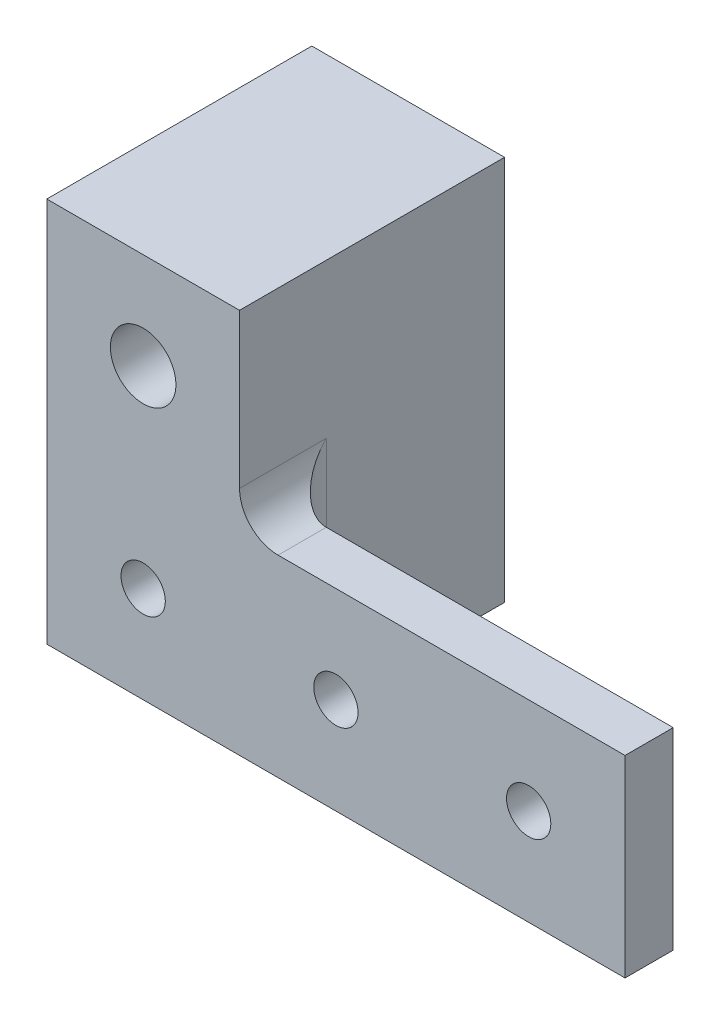
SolidWorks part; units mm, degrees
ref_plane "Front Plane" through (0, 0, 0) normal (0, 0, 1) x (1, 0, 0)
ref_plane "Top Plane" through (0, 0, 0) normal (0, 1, 0) x (1, 0, 0)
ref_plane "Right Plane" through (0, 0, 0) normal (1, 0, 0) x (0, 0, -1)
sketch "Sketch1" plane through (0, 0, 0) normal (0, 0, 1) x (1, 0, 0)
  line L0 (0, 0) -> (0, 50.8)
  line L1 (0, 50.8) -> (25.4, 50.8)
  line L2 (25.4, 50.8) -> (25.4, 25.4)
  line L3 (25.4, 25.4) -> (76.2, 25.4)
  line L4 (76.2, 25.4) -> (76.2, 0)
  line L5 (76.2, 0) -> (0, 0)
  dimension "D1" = 50.8
  dimension "D2" = 25.4
  dimension "3" = 76.2
extrude "Boss-Extrude1" add sketch "Sketch1" along normal blind 34.925
sketch "Sketch2" plane through (0, 0, 34.925) normal (0, 0, 1) x (1, 0, 0)
  line L0 (25.4, 50.8) -> (0, 50.8) construction
  line L1 (25.4, 25.4) -> (25.4, 50.8) construction
  line L2 (0, 0) -> (76.2, 0) construction
  circle A0 centre (12.7, 38.1) radius 2.921
  circle A1 centre (12.7, 12.7) radius 2.921
  circle A2 centre (38.1, 12.7) radius 2.921
  circle A3 centre (63.5, 12.7) radius 2.921
  dimension ".23" = 5.842
  dimension "D2" = 12.7
  dimension "D3" = 12.7
  dimension "D4" = 12.7
  dimension "D5" = 3
extrude "Cut-Extrude1" cut sketch "Sketch2" against normal through all
sketch "Sketch3" plane through (0, 0, 34.925) normal (0, 0, 1) x (1, 0, 0)
  line L0 (25.4, 50.8) -> (0, 50.8) construction
  line L1 (0, 0) -> (4.7625, 0)
  line L2 (0, 0) -> (0, 50.8)
  line L3 (0, 50.8) -> (4.7625, 50.8)
  line L4 (4.7625, 0) -> (4.7625, 50.8)
  dimension "D1" = 4.7625
sketch "Sketch4" plane through (0, 0, 0) normal (0, -1, 0) x (1, 0, 0)
  line L1 (76.2, 0) -> (25.4, 0)
  line L2 (76.2, 0) -> (76.2, 28.575)
  line L3 (76.2, 28.575) -> (25.4, 28.575)
  line L4 (25.4, 0) -> (25.4, 28.575)
  dimension "D1" = 28.575
  dimension "D2" = 50.8
extrude "Cut-Extrude3" cut sketch "Sketch4" against normal through all
fillet "Fillet1" radius 5.08 2 edges at (25.4, 12.7, 28.575) (25.4, 25.4, 31.75)
sketch "Sketch5" plane through (0, 0, 34.925) normal (0, 0, 1) x (1, 0, 0)
  circle A0 centre (12.7, 38.1) radius 4.318
  dimension "0." = 8.636
extrude "Cut-Extrude4" cut sketch "Sketch5" against normal blind 12.7
